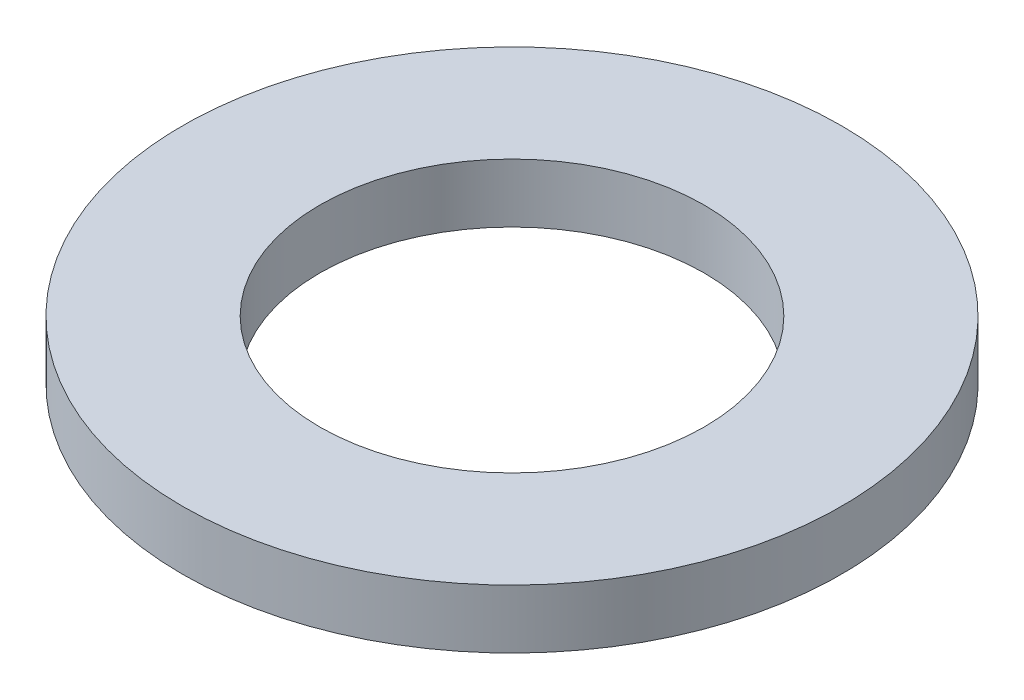
SolidWorks part; units mm, degrees
ref_plane "Front Plane" through (0, 0, 0) normal (0, 0, 1) x (1, 0, 0)
ref_plane "Top Plane" through (0, 0, 0) normal (0, 1, 0) x (1, 0, 0)
ref_plane "Right Plane" through (0, 0, 0) normal (1, 0, 0) x (0, 0, -1)
sketch "Sketch1" plane through (0, 0, 0) normal (0, 1, 0) x (1, 0, 0)
  circle A0 centre (0, 0) radius 19.05
  dimension "OD" = 38.1
extrude "Boss-Extrude1" add sketch "Sketch1" along normal blind 3.4036
sketch "Sketch5" plane through (0, 3.4036, 0) normal (0, 1, 0) x (-1, 0, 0)
  circle A0 centre (0, 0) radius 11.1125
  dimension "ID" = 22.225
extrude "Cut-Extrude1" cut sketch "Sketch5" against normal through all
